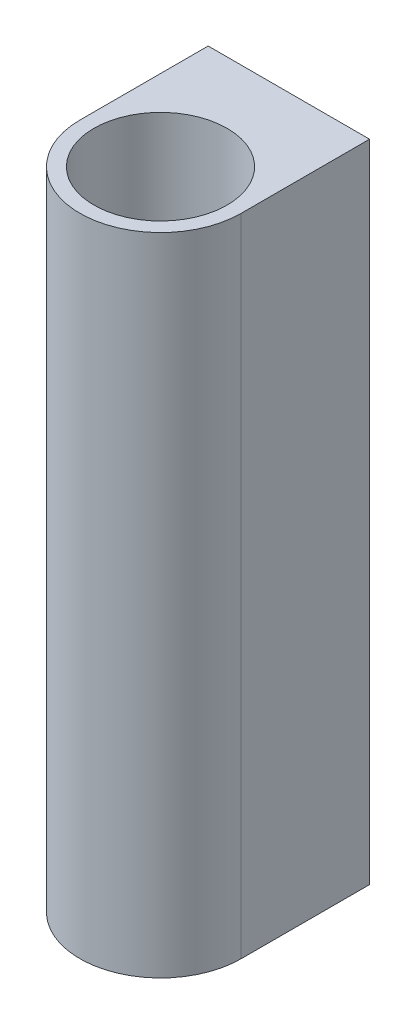
SolidWorks part; units mm, degrees
other "DetailItem2"
other "DetailItem3"
material "6061 Alloy"
ref_plane "Front Plane" through (0, 0, 0) normal (0, 0, 1) x (1, 0, 0)
ref_plane "Top Plane" through (0, 0, 0) normal (0, 1, 0) x (1, 0, 0)
ref_plane "Right Plane" through (0, 0, 0) normal (1, 0, 0) x (0, 0, -1)
sketch "Sketch11" plane through (0, 0, 0) normal (0, 0, 1) x (1, 0, 0)
  line L0 (0, 0) -> (0, 109.6398) construction
  line L1 (0, 0) -> (-89.1372, 0) construction
sketch "Sketch12" plane through (0, 0, 0) normal (0, 0, 1) x (1, 0, 0)
  line L0 (-25.4, 0) -> (-25.4, 203.2)
  line L1 (200000, 0) -> (-200089.1372, 0) construction
  line L4 (-20.955, 0) -> (-25.4, 0)
  line L5 (-20.955, 0) -> (-20.955, 38.1)
  line L6 (-20.955, 38.1) -> (-19.177, 38.1)
  line L7 (-19.177, 38.1) -> (-19.177, 165.1)
  line L8 (-19.177, 165.1) -> (-20.955, 165.1)
  line L9 (-20.955, 165.1) -> (-20.955, 203.2)
  line L10 (-20.955, 203.2) -> (-25.4, 203.2)
  line L12 (0, -200000) -> (0, 200109.6398) construction
  line L13 (-20.955, 203.2) -> (-15.875, 203.2) construction
  line L14 (-15.875, 203.2) -> (-15.875, 0) construction
  line L15 (-15.875, 0) -> (-20.955, 0) construction
  dimension "D1" = 25.4
  dimension "D2" = 20.955
  dimension "D3" = 19.177
  dimension "D4" = 38.1
  dimension "D5" = 203.2
  dimension "D6" = 4.445
  dimension "D7" = 15.875
revolve "Revolve1" add sketch "Sketch12" angle 360 about L0
ref_plane "mideplane" through (0, 101.6, 0) normal (0, -1, 0) x (-1, 0, 0)
ref_plane "top pipe plane" through (0, 0, 0) normal (0, -1, 0) x (-1, 0, 0)
ref_plane "bottom pipe plane" through (0, 203.2, 0) normal (0, 1, 0) x (1, 0, 0)
ref_plane "pipe support midplane" through (0, 101.6, 0) normal (0, -1, 0) x (-1, 0, 0)
sketch "Sketch13" plane through (0, 0, 0) normal (0, -1, 0) x (-1, 0, 0)
  line L0 (0, 0) -> (0, 40.4) construction
  line L1 (0, 40.4) -> (0, 25.4) construction
  line L6 (-25.4, 40.4) -> (25.4, 40.4)
  line L8 (12.5848, 40.4) -> (22.5848, 40.4)
  line L9 (12.5848, 40.4) -> (12.5848, 25.4) construction
  line L10 (12.5848, 25.4) -> (22.5848, 25.4) construction
  line L11 (22.5848, 40.4) -> (22.5848, 25.4) construction
  line L19 (25.4, 0) -> (25.4, 40.4)
  line L20 (-25.4, 0) -> (-25.4, 40.4)
  circle A0 centre (0, 0) radius 25.4 construction
  circle A1 centre (0, 0) radius 25.4
  dimension "D2" = 15
  dimension "D1" = 15
  dimension "D3" = 10
extrude "Boss-Extrude1" add sketch "Sketch13" against normal up to surface (203.2 mm away) contours A1 L19 L6 L20 up to face at (0, 203.2, -25.4)
sketch "Sketch15" plane through (0, 0, -40.4) normal (0, 0, -1) x (-1, 0, 0)
  line L0 (0, 0) -> (0, 203.2) construction
  line L1 (25.4, 203.2) -> (-25.4, 203.2) construction
  line L2 (0, 30) -> (-25.4, 30) construction
  line L5 (-25.4, 203.2) -> (-25.4, 0) construction
  line L7 (0, 173.2) -> (-25.4, 173.2) construction
  line L8 (-25.4, 0) -> (25.4, 0) construction
  circle A0 centre (-12.7, 30) radius 5
  circle A1 centre (-12.7, 173.2) radius 5
  dimension "D1" = 10
  dimension "D2" = 30
  dimension "D3" = 30
extrude "Cut-Extrude1" cut sketch "Sketch15" against normal blind 15
mirror "Mirror1" about plane through (0, 0, 0) normal (1, 0, 0) of "Cut-Extrude1"
